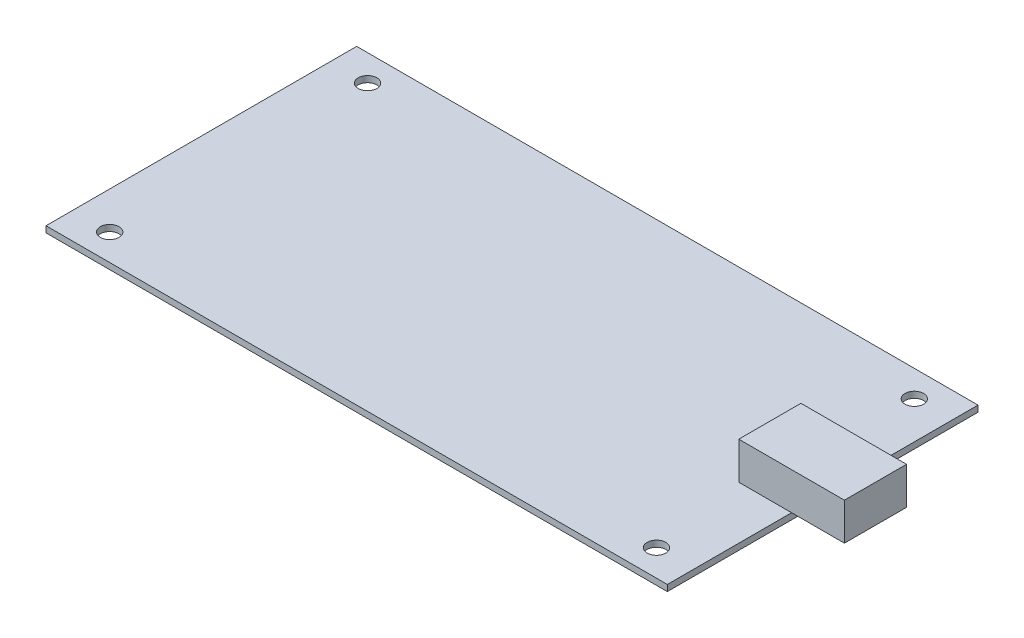
SolidWorks part; units mm, degrees
material "PBT 一般用途"
ref_plane "前视基准面" through (0, 0, 0) normal (0, 0, 1) x (1, 0, 0)
ref_plane "上视基准面" through (0, 0, 0) normal (0, 1, 0) x (1, 0, 0)
ref_plane "右视基准面" through (0, 0, 0) normal (1, 0, 0) x (0, 0, -1)
sketch "草图1" plane through (0, 0, 0) normal (0, 1, 0) x (1, 0, 0)
  line L1 (-50, -25) -> (50, -25)
  line L2 (-50, -25) -> (-50, 25)
  line L3 (-50, 25) -> (50, 25)
  line L4 (50, -25) -> (50, 25)
  line L5 (-50, -25) -> (50, 25) construction
  line L6 (-50, 25) -> (50, -25) construction
  point P0 (0, 0)
  dimension "D1" = 100
  dimension "D2" = 50
extrude "凸台-拉伸1" add sketch "草图1" along normal blind 1
sketch "草图2" plane through (0, 1, 0) normal (0, 1, 0) x (1, 0, 0)
  line L0 (50, -25) -> (50, 25) construction
  line L1 (41.5, -5) -> (58.5, -5)
  line L2 (41.5, -5) -> (41.5, 5)
  line L3 (41.5, 5) -> (58.5, 5)
  line L4 (58.5, -5) -> (58.5, 5)
  line L5 (41.5, -5) -> (58.5, 5) construction
  line L6 (41.5, 5) -> (58.5, -5) construction
  point P0 (50, 0)
  dimension "D1" = 17
  dimension "D2" = 10
extrude "凸台-拉伸2" add sketch "草图2" along normal blind 6
sketch "草图3" plane through (0, 1, 0) normal (0, 1, 0) x (1, 0, 0)
  line L1 (-44, 20.75) -> (44, 20.75)
  line L2 (-44, 20.75) -> (-44, -20.75)
  line L3 (-44, -20.75) -> (44, -20.75)
  line L4 (44, 20.75) -> (44, -20.75)
  line L5 (-44, 20.75) -> (44, -20.75) construction
  line L6 (-44, -20.75) -> (44, 20.75) construction
  point P0 (0, 0)
  dimension "D1" = 88
  dimension "D2" = 41.5
sketch "草图4" plane through (0, 1, 0) normal (0, 1, 0) x (1, 0, 0)
  point P0 (-44, 20.75)
  point P3 (-44, -20.75)
  point P6 (44, -20.75)
  point P9 (44, 20.75)
hole_wizard "孔1" positions "草图4" profile "草图5" legacy end condition through all
sketch "草图5" plane through (-44, 1, -20.75) normal (1, 0, 0) x (0, 0, 1)
  line L0 (0, 0) -> (0, 1)
  line L1 (0, 1) -> (1.5, 1)
  line L2 (1.5, 1) -> (1.5, 0)
  line L3 (1.5, 0) -> (0, 0)
  line L4 (0, 110) -> (0, -10) construction
  dimension "直径" = 3
  dimension "深度" = 1
